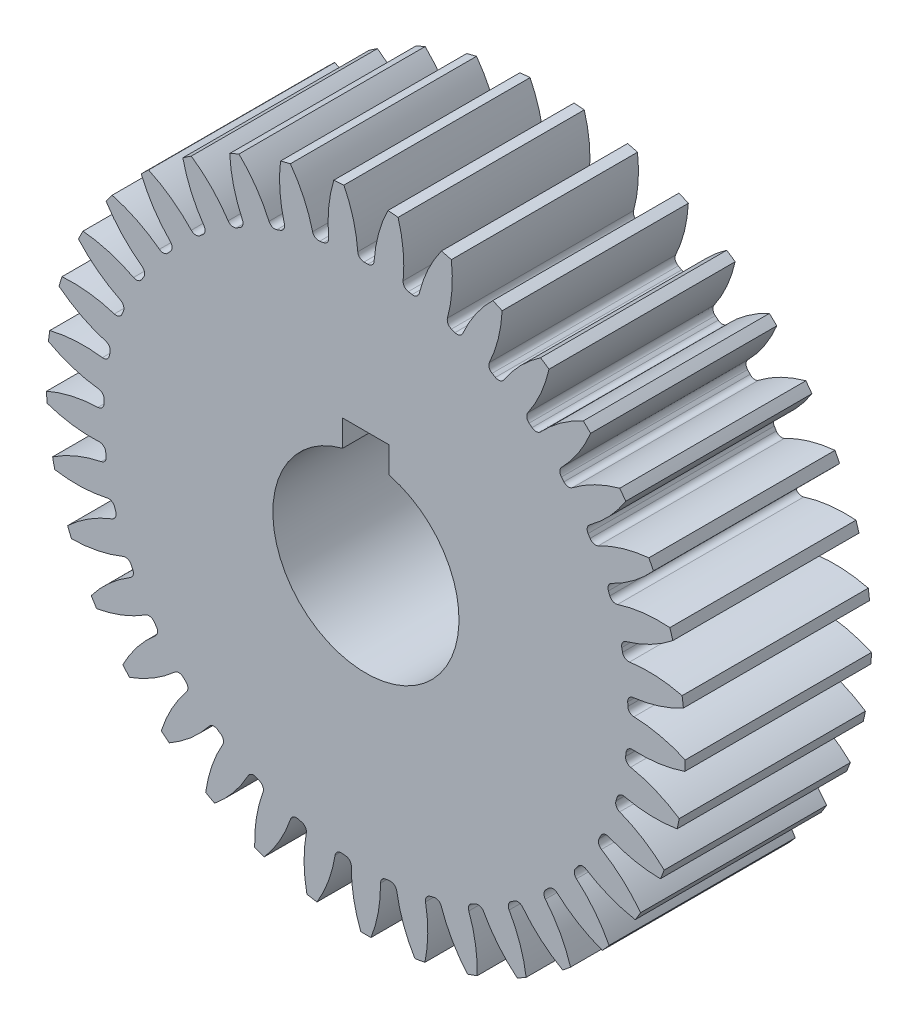
SolidWorks part; units mm, degrees
ref_plane "Front Plane" through (0, 0, 0) normal (1, 0, 0) x (0, 1, 0)
ref_plane "Top Plane" through (0, 0, 0) normal (0, 0, 1) x (0, 1, 0)
ref_plane "Right Plane" through (0, 0, 0) normal (0, 1, 0) x (-1, 0, 0)
sketch "Sketch1" plane through (0, 0, 0) normal (0, 0, 1) x (0, 1, 0)
  circle A0 centre (0, 0) radius 10
  circle A1 centre (0, 0) radius 34.32
  dimension "D1" = 20
  dimension "D2" = 68.64
extrude "Boss-Extrude2" add sketch "Sketch1" along normal blind 20 contours A0 | A1
sketch "Sketch2" plane through (0, 0, 20) normal (0, 0, 1) x (1, 0, 0)
  line L0 (0, 0) -> (0, 34.32) construction
  line L1 (-0.845, 28.1473) -> (0, 0) construction
  line L2 (0, 26.154) -> (-1.9613, 34.0201) construction
  circle A0 centre (0, 0) radius 34.32 construction
  arc A1 (-0.845, 28.1473) -> (-2.3637, 34.2385) centre (-15.5957, 27.7045) ccw
  arc A2 (2.3637, 34.2385) -> (-2.3637, 34.2385) centre (0, 0) ccw
  arc A3 (1.6456, 32.5184) -> (-1.6456, 32.5184) centre (0, 0) ccw
  arc A4 (0.845, 28.1473) -> (-0.845, 28.1473) centre (0, 0) ccw
  arc A5 (0.845, 28.1473) -> (2.3637, 34.2385) centre (15.5957, 27.7045) cw
  point P14 (-1.2767, 31.2746)
  dimension "D1" = 68.64
  dimension "D2" = 65.12
  dimension "D3" = 6.16
  dimension "D4" = 14
  dimension "D5" = 3.2926
extrude "Cut-Extrude1" cut sketch "Sketch2" against normal through all contours A2 A1 A4 A5
fillet "Fillet1" radius 0.6688 2 edges at (-0.845, 28.1473, 10) (0.845, 28.1473, 10)
pattern_circular "CirPattern1" count 37 over 360 about axis through (0, 0, 0) along (0, 0, 1) of "Fillet1", "Cut-Extrude1"
sketch "Sketch3" plane through (0, 0, 20) normal (0, 0, 1) x (1, 0, 0)
  line L2 (-2.5, 12.5) -> (2.5, 12.5)
  line L3 (-2.5, 12.5) -> (-2.5, 9.6825)
  line L5 (2.5, 12.5) -> (2.5, 9.6825)
  line L6 (-2.5, 12.5) -> (0, 10) construction
  line L7 (0, 10) -> (2.5, 12.5) construction
  circle A0 centre (0, 0) radius 10 construction
  arc A1 (2.5, 9.6825) -> (-2.5, 9.6825) centre (0, 0) ccw
  dimension "D1" = 5
extrude "Cut-Extrude2" cut sketch "Sketch3" against normal through all
sketch "Sketch7" plane through (0, 0, 20) normal (0, 0, 1) x (1, 0, 0)
  line L0 (-2.8903, 34.8805) -> (2.8903, 34.8805) construction
  line L1 (0, 28.875) -> (0, 34.8805) construction
  line L2 (-2.072, 34.8805) -> (-0.7209, 30.1735) construction
  line L3 (2.072, 34.8805) -> (0.7209, 30.1735) construction
  arc A0 (-2.3637, 34.2385) -> (-3.4566, 34.1455) centre (0, 0) ccw construction
  arc A1 (3.4566, 34.1455) -> (2.3637, 34.2385) centre (0, 0) ccw construction
  arc A2 (0.2056, 28.1592) -> (-0.2056, 28.1592) centre (0, 0) ccw construction
  arc A3 (-0.7209, 30.1735) -> (0.7209, 30.1735) centre (0, 30.3805) ccw
  circle A4 centre (0, 0) radius 35
  dimension "D1" = 4.5
  dimension "D3" = 5.7871
  dimension "D2" = 1.5
  dimension "D4" = 4.1439
equation "\"No of teeth\"= 37"
equation "\"Module\"= 1.76"
equation "\"Bore Diameter\"=20"
equation "\"Pressure Angle\"= 14"
equation "\"Outer Diameter\"= ( \"No of teeth\" + 2 ) * \"Module\""
equation "\"Pitch Diameter\"= \"No of teeth\" * \"Module\""
equation "\"Backlash\"= 0.3 * \"Module\""
equation "\"Arc Length\"= ( ( \"Module\" * pi ) / 2 ) + \"Backlash\""
equation "\"Fillet Radius\"= 0.38 * \"Module\""
equation "\"Tooth Depth\"= IIF ( \"Module\" <= 1.25 , \"Module\" * 3.5 , \"Module\" * 3.5 )"
equation "\"D1@Sketch1\"=\"Bore Diameter\""
equation "\"D2@Sketch1\"=\"Outer Diameter\""
equation "\"D1@Sketch2\"=\"Outer Diameter\""
equation "\"D2@Sketch2\"=\"Pitch Diameter\""
equation "\"D3@Sketch2\"=\"Tooth Depth\""
equation "\"D4@Sketch2\"=\"Pressure Angle\""
equation "\"D5@Sketch2\"=\"Arc Length\""
equation "\"D1@Fillet1\"=\"Fillet Radius\""
equation "\"D1@CirPattern1\"=\"No of teeth\""
